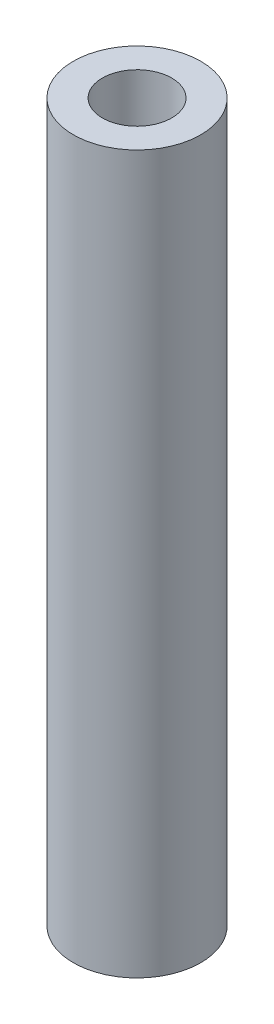
SolidWorks part; units mm, degrees
ref_plane "Alzado" through (0, 0, 0) normal (0, 0, 1) x (1, 0, 0)
ref_plane "Planta" through (0, 0, 0) normal (0, 1, 0) x (1, 0, 0)
ref_plane "Vista lateral" through (0, 0, 0) normal (1, 0, 0) x (0, 0, -1)
sketch "Croquis1" plane through (0, 0, 0) normal (0, 1, 0) x (1, 0, 0)
  circle A0 centre (0, 0) radius 4
  circle A1 centre (0, 0) radius 2.175
  dimension "D1" = 8
  dimension "D2" = 4.35
extrude "Saliente-Extruir1" add sketch "Croquis1" along normal blind 45
